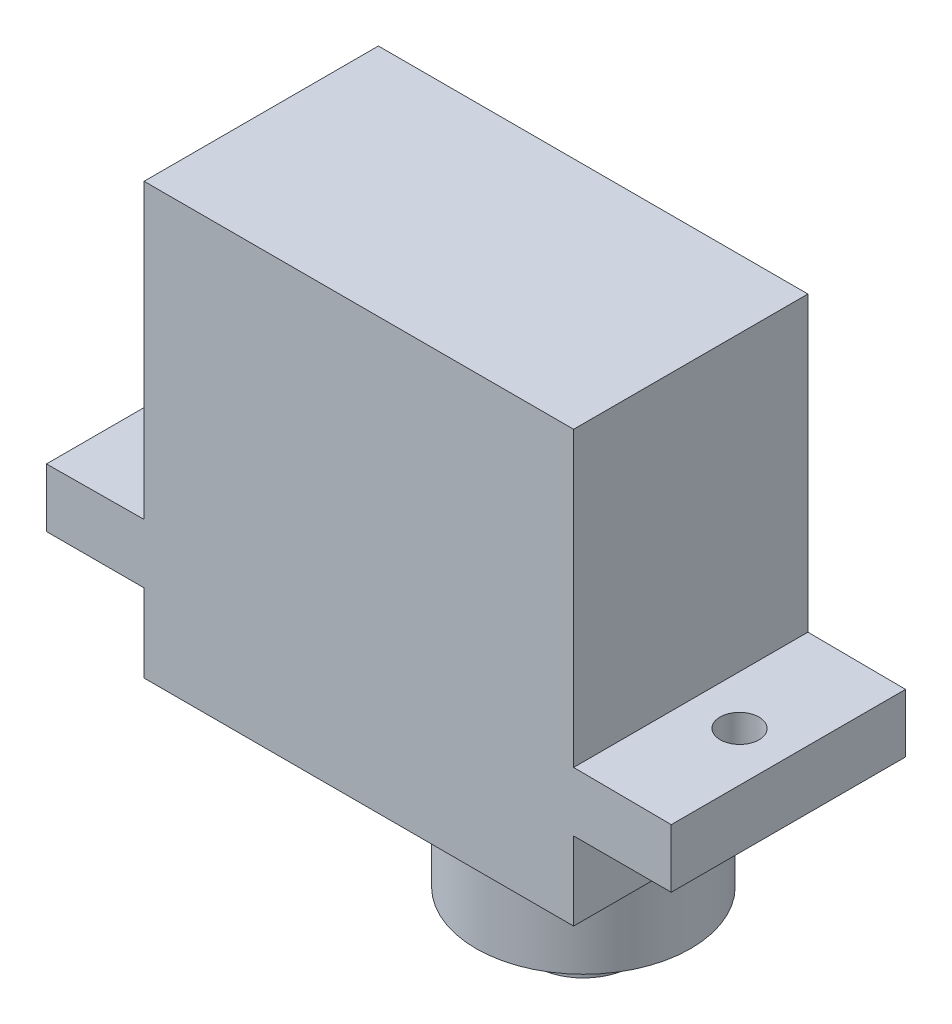
SolidWorks part; units mm, degrees
ref_plane "Alzado" through (0, 0, 0) normal (0, 0, 1) x (1, 0, 0)
ref_plane "Planta" through (0, 0, 0) normal (0, 1, 0) x (1, 0, 0)
ref_plane "Vista lateral" through (0, 0, 0) normal (1, 0, 0) x (0, 0, -1)
sketch "Croquis1" plane through (0, 0, 0) normal (0, 0, 1) x (1, 0, 0)
  line L0 (0, -10.537) -> (0, 10.537) construction
  line L1 (-16, -7.537) -> (-11, -7.5)
  line L2 (-11, -7.5) -> (-11, 7.5)
  line L3 (-11, 7.5) -> (11, 7.5)
  line L4 (11, -7.5) -> (11, 7.5)
  line L5 (-11, -7.5) -> (11, 7.5) construction
  line L6 (-11, 7.5) -> (11, -7.5) construction
  line L7 (11, -7.5) -> (16, -7.537)
  line L8 (-16, -7.537) -> (-16, -10.537)
  line L9 (-16, -10.537) -> (-11, -10.537)
  line L10 (16, -7.537) -> (16, -10.537)
  line L11 (5.5, -20.8225) -> (5.5, -25.056) construction
  line L13 (11, -10.537) -> (11, -14.537)
  line L14 (0, -14.537) -> (-11, -14.537)
  line L15 (-11, -10.537) -> (-11, -14.537)
  line L16 (11, -10.537) -> (16, -10.537)
  line L17 (11, -14.537) -> (11, -18.537)
  line L18 (11, -18.537) -> (8, -18.537)
  line L19 (0, -14.537) -> (0, -18.537)
  line L21 (8, -18.537) -> (8, -20.8225)
  line L22 (8, -20.8225) -> (3, -20.8225)
  line L23 (3, -18.537) -> (3, -20.8225)
  line L24 (3, -18.537) -> (0, -18.537)
  point P0 (0, 0)
  dimension "D1" = 15
  dimension "D2" = 22
  dimension "D3" = 3
  dimension "D4" = 32
  dimension "D5" = 4
  dimension "D6" = 4
  dimension "D7" = 5.5
  dimension "D8" = 0
  dimension "D9" = 11
  dimension "D10" = 0
  dimension "D11" = 5
extrude "Saliente-Extruir1" add sketch "Croquis1" along normal blind 12
sketch "Croquis2" plane through (0, -20.8225, 0) normal (0, -1, 0) x (1, 0, 0)
  line L0 (0, 6) -> (11, 6) construction
  line L1 (0, 12) -> (0, 0) construction
  line L2 (11, 12) -> (11, 0) construction
  circle A0 centre (5.5, 6) radius 5.5
extrude "Cortar-Extruir1" cut sketch "Croquis2" against normal up to surface (6.2855 mm away) flip side to cut up to face at (-5.5, -14.537, 6)
sketch "Croquis3" plane through (0, -20.8225, 0) normal (0, -1, 0) x (1, 0, 0)
  line L0 (3, 6) -> (8, 6) construction
  line L1 (3, 10.899) -> (3, 1.101) construction
  line L2 (8, 10.899) -> (8, 1.101) construction
  circle A0 centre (5.5, 6) radius 2.5
extrude "Cortar-Extruir2" cut sketch "Croquis3" against normal up to surface (2.2855 mm away) flip side to cut up to face at (1.5, -18.537, 6)
sketch "Croquis4" plane through (0, -10.537, 0) normal (0, -1, 0) x (1, 0, 0)
  line L0 (0, 0) -> (0, 17.049) construction
  line L1 (-16, 12) -> (-16, 0) construction
  circle A0 centre (-13.5, 6) radius 1
  circle A1 centre (13.5, 6) radius 1
  dimension "D1" = 2
  dimension "D2" = 2.5
extrude "Cortar-Extruir3" cut sketch "Croquis4" against normal blind 12
